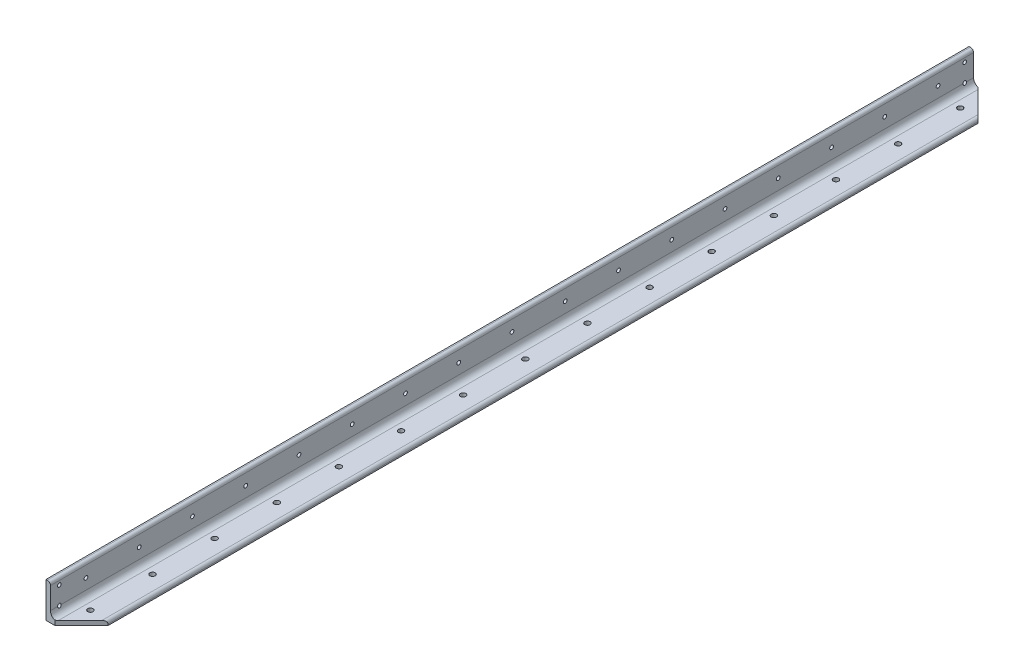
SolidWorks part; units mm, degrees
material "1.0037 (S235JR)"
ref_plane "Ebene vorne" through (0, 0, 0) normal (0, 0, 1) x (1, 0, 0)
ref_plane "Ebene oben" through (0, 0, 0) normal (0, 1, 0) x (1, 0, 0)
ref_plane "Ebene rechts" through (0, 0, 0) normal (1, 0, 0) x (0, 0, -1)
sketch "Skizze1" plane through (0, 0, 0) normal (0, 0, 1) x (1, 0, 0)
  line L0 (0, 40) -> (0, 0)
  line L1 (0, 0) -> (40, 0)
  line L2 (40, 0) -> (40, 1.5)
  line L3 (36.5, 5) -> (12, 5)
  line L4 (5, 12) -> (5, 36.5)
  line L5 (1.5, 40) -> (0, 40)
  arc A0 (5, 36.5) -> (1.5, 40) centre (1.5, 36.5) ccw
  arc A1 (40, 1.5) -> (36.5, 5) centre (36.5, 1.5) ccw
  arc A2 (12, 5) -> (5, 12) centre (12, 12) cw
  dimension "D5" = 3.5
  dimension "D6" = 7
  dimension "D1" = 40
  dimension "D2" = 40
  dimension "D3" = 5
  dimension "D4" = 5
extrude "Aufsatz-Linear austragen1" add sketch "Skizze1" along normal blind 1040
sketch "Skizze2" plane through (0, 5, 0) normal (0, 1, 0) x (1, 0, 0)
  line L0 (36.5, -520) -> (151.874, -520) construction
  line L5 (36.5, -1040) -> (36.5, 0) construction
  line L6 (10, -1040) -> (40, -1010)
  line L7 (36.5, -1040) -> (12, -1040) construction
  line L8 (40, -1040) -> (40, 0) construction
  line L9 (40, -1010) -> (40, -1040)
  line L10 (40, -1040) -> (10, -1040)
  line L11 (10, 0) -> (40, -30)
  line L12 (40, 0) -> (10, 0)
  line L13 (40, -30) -> (40, 0)
  dimension "D1" = 30
  dimension "D2" = 30
extrude "Schnitt-Linear austragen1" cut sketch "Skizze2" against normal blind 10 and the other way blind 10
sketch "Skizze3" plane through (0, 5, 0) normal (0, 1, 0) x (1, 0, 0)
  line L0 (20, 17.5614) -> (20, -1061.3162) construction
  line L1 (0, -1040) -> (0, 0) construction
  circle A0 centre (20, -30) radius 3
  circle A1 centre (20, -30) radius 5 construction
  dimension "D1" = 6
  dimension "D4" = 10
  dimension "D2" = 20
  dimension "D3" = 30
extrude "Schnitt-Linear austragen2" cut sketch "Skizze3" against normal blind 10
pattern_linear "Lineares Muster1" count 15 spacing 70 along (0, 0, 1) of "Schnitt-Linear austragen2"
hole_wizard "M5 Gewindebohrung1" positions "Skizze4" profile "Skizze5" tap size "M5" standard "DIN"
sketch "Skizze4" plane through (0, 0, 0) normal (-1, 0, 0) x (0, 0, 1)
  line L0 (1040, 40) -> (1040, 0) construction
  line L1 (1040, 40) -> (0, 40) construction
  point P0 (1000, 24)
  dimension "D1" = 40
  dimension "D2" = 16
sketch "Skizze5" plane through (0, 24, 1000) normal (0, 1, 0) x (0, 0, 1)
  line L0 (0, 0) -> (0, 15.2618)
  line L1 (0, 15.2618) -> (2.1, 14)
  line L2 (2.1, 14) -> (2.1, 0)
  line L5 (2.1, 0) -> (0, 0)
  line L10 (0, 15.2618) -> (-2.1, 14) construction
  line L11 (0, -6.35) -> (0, 107.95) construction
  dimension "Bohrerdurchmesser" = 4.2
  dimension "Bohrungstiefe" = 14
  dimension "Spitzenwinkel" = 118
pattern_linear "Lineares Muster2" count 17 spacing 60 along (0, 0, -1) of "M5 Gewindebohrung1"
hole_wizard "M5 Gewindebohrung2" positions "Skizze6" profile "Skizze7" tap size "M5" standard "DIN"
sketch "Skizze6" plane through (0, 0, 0) normal (-1, 0, 0) x (0, 0, 1)
  line L0 (520, 0) -> (520, 103.658) construction
  line L1 (1040, 0) -> (0, 0) construction
  line L2 (1030, 12) -> (1030, 32) construction
  line L3 (1040, 40) -> (0, 40) construction
  line L4 (1040, 40) -> (1040, 0) construction
  point P10 (1030, 12)
  point P11 (1030, 32)
  point P25 (0, 0)
  point P26 (10, 12)
  point P27 (10, 32)
  dimension "D1" = 8
  dimension "D2" = 12
  dimension "D3" = 10
sketch "Skizze7" plane through (0, 32, 10) normal (0, 1, 0) x (0, 0, 1)
  line L0 (0, 0) -> (0, 15.2618)
  line L1 (0, 15.2618) -> (2.1, 14)
  line L2 (2.1, 14) -> (2.1, 0)
  line L5 (2.1, 0) -> (0, 0)
  line L10 (0, 15.2618) -> (-2.1, 14) construction
  line L11 (0, -6.35) -> (0, 107.95) construction
  dimension "Bohrerdurchmesser" = 4.2
  dimension "Bohrungstiefe" = 14
  dimension "Spitzenwinkel" = 118
